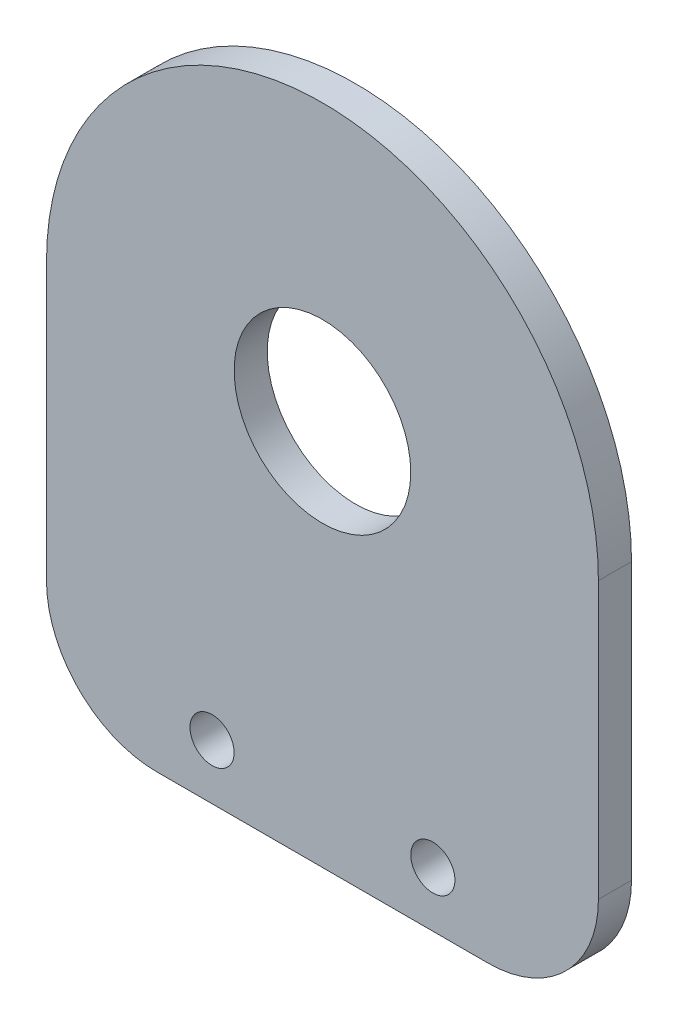
SolidWorks part; units mm, degrees
material "6061 合金"
ref_plane "正面" through (0, 0, 0) normal (0, 0, 1) x (1, 0, 0)
ref_plane "平面" through (0, 0, 0) normal (0, 1, 0) x (1, 0, 0)
ref_plane "右側面" through (0, 0, 0) normal (1, 0, 0) x (0, 0, -1)
sketch "ｽｹｯﾁ1" plane through (0, 0, 0) normal (0, 0, 1) x (1, 0, 0)
  line L0 (-25, -12.5) -> (25, -12.5) construction
  line L1 (25, -17.5) -> (-25, -17.5)
  line L2 (25, -17.5) -> (25, 17.5)
  line L4 (-25, -17.5) -> (-25, 17.5)
  line L5 (25, -17.5) -> (-25, 17.5) construction
  line L6 (25, 17.5) -> (-25, -17.5) construction
  arc A1 (25, 17.5) -> (-25, 17.5) centre (0, 17.5) ccw
  circle A2 centre (0, 17.5) radius 8
  circle A3 centre (-10, -12.5) radius 2
  circle A4 centre (10, -12.5) radius 2
  point P0 (0, 0)
  point P14 (0, -12.5)
  dimension "D3" = 25
  dimension "D4" = 16
  dimension "D5" = 10
  dimension "D6" = 20
  dimension "D7" = 4
  dimension "D1" = 50
  dimension "D2" = 35
  dimension "D8" = 5
extrude "ﾎﾞｽ - 押し出し1" add sketch "ｽｹｯﾁ1" along normal blind 3
fillet "ﾌｨﾚｯﾄ1" radius 10 2 edges at (25, -17.5, 1.5) (-25, -17.5, 1.5)
